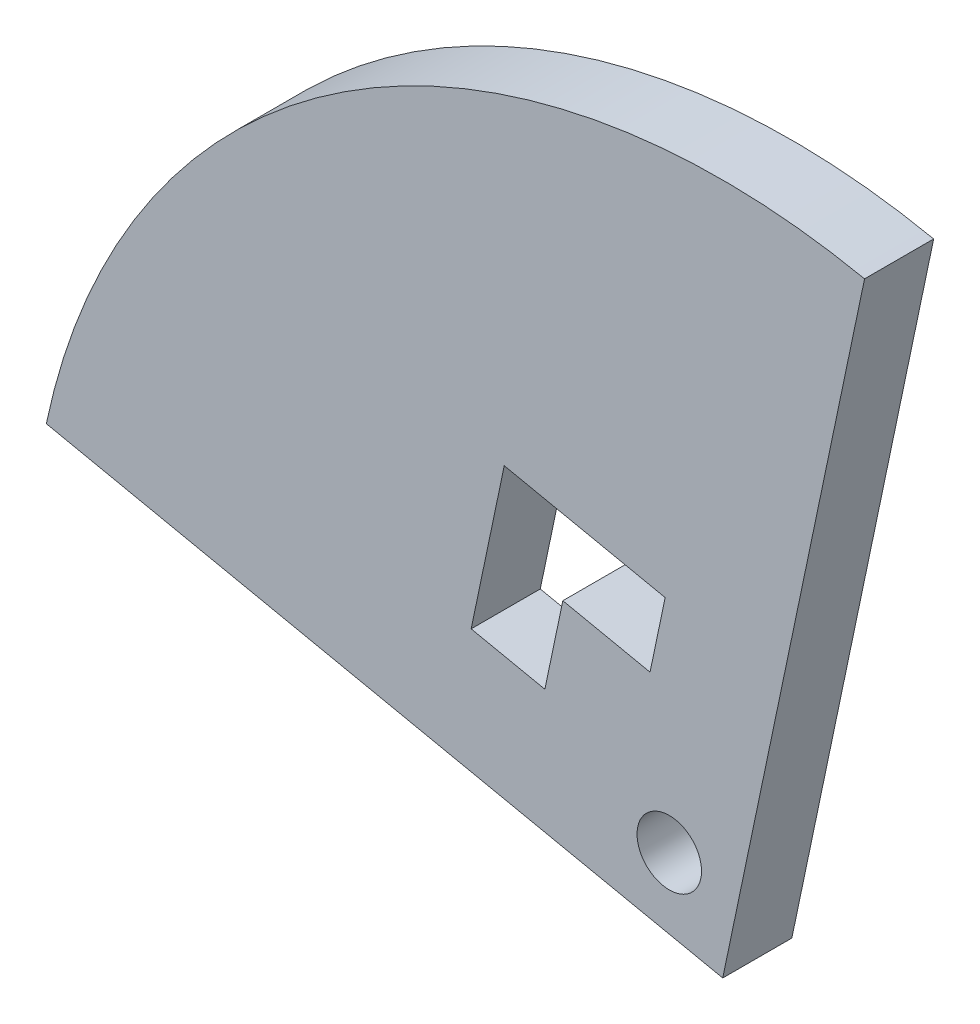
SolidWorks part; units mm, degrees
ref_plane "Front Plane" through (0, 0, 0) normal (0, 0, 1) x (1, 0, 0)
ref_plane "Top Plane" through (0, 0, 0) normal (0, 1, 0) x (1, 0, 0)
ref_plane "Right Plane" through (0, 0, 0) normal (1, 0, 0) x (0, 0, -1)
sketch "Sketch2" plane through (0, 0, 0) normal (0, 0, 1) x (1, 0, 0)
  line L0 (-11.2209, 59.4953) -> (-19.0396, 22.2062)
  line L1 (-19.0396, 22.2062) -> (-56.3287, 30.0249)
  arc A0 (-11.2209, 59.4953) -> (-56.3287, 30.0249) centre (-19.0396, 22.2062) ccw
extrude "Boss-Extrude2" add sketch "Sketch2" along normal blind 3.81
sketch "Sketch3" plane through (0, 0, 3.81) normal (0, 0, 1) x (1, 0, 0)
  line L0 (-19.0396, 22.2062) -> (-11.2209, 59.4953) construction
  line L1 (-56.3287, 30.0249) -> (-19.0396, 22.2062) construction
  circle A0 centre (-21.9866, 26.717) radius 1.778
  dimension "D1" = 3.81
  dimension "D2" = 3.81
extrude "Cut-Extrude1" cut sketch "Sketch3" against normal through all
sketch "Sketch4" plane through (0, 0, 0) normal (0, 0, -1) x (-1, 0, 0)
  line L0 (19.0396, 22.2062) -> (15.8441, 37.4462) construction
  line L2 (19.0396, 22.2062) -> (11.2209, 59.4953) construction
  line L3 (15.8441, 37.4462) -> (31.0841, 40.6417) construction
  line L4 (31.0841, 40.6417) -> (34.2796, 25.4017) construction
  line L5 (56.3287, 30.0249) -> (19.0396, 22.2062) construction
  line L6 (31.0841, 40.6417) -> (31.9181, 36.6642)
  line L7 (31.0841, 40.6417) -> (22.213, 38.7816)
  line L8 (31.9181, 36.6642) -> (23.047, 34.8041)
  line L9 (22.213, 38.7816) -> (23.047, 34.8041)
  line L10 (27.8541, 35.8121) -> (28.8444, 31.0888)
  line L11 (27.8541, 35.8121) -> (31.9181, 36.6642)
  line L12 (28.8444, 31.0888) -> (32.9084, 31.9409)
  line L13 (31.9181, 36.6642) -> (32.9084, 31.9409)
  dimension "D1" = 15.24
  dimension "D2" = 15.24
  dimension "D3" = 4.064
  dimension "D4" = 0
  dimension "D5" = 4.064
  dimension "D6" = 8.8711
  dimension "D7" = 8.89
extrude "Cut-Extrude2" cut sketch "Sketch4" against normal through all contours L7 L9 L8 L6 | L13 L8 L10 L12
